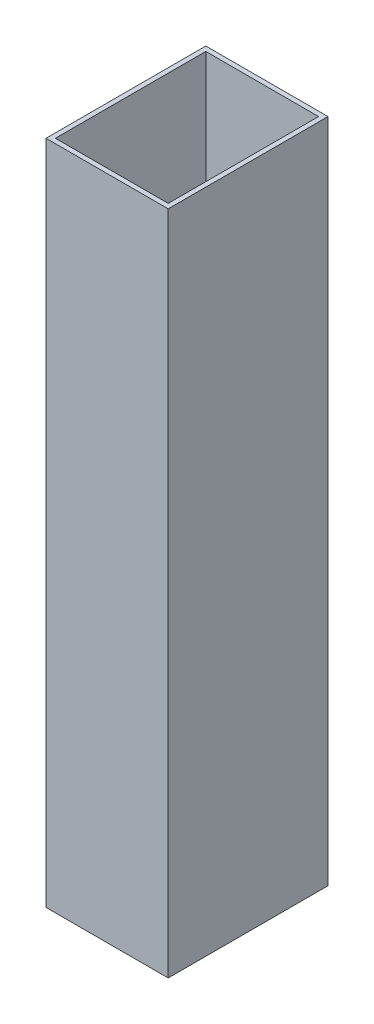
SolidWorks part; units mm, degrees
ref_plane "Plan de face" through (0, 0, 0) normal (0, 0, 1) x (1, 0, 0)
ref_plane "Plan de dessus" through (0, 0, 0) normal (0, 1, 0) x (1, 0, 0)
ref_plane "Plan de droite" through (0, 0, 0) normal (1, 0, 0) x (0, 0, -1)
sketch "Esquisse1" plane through (0, 0, 0) normal (0, 0, 1) x (1, 0, 0)
  line L1 (-41.275, 225) -> (41.275, 225)
  line L2 (-41.275, 225) -> (-41.275, -225)
  line L3 (-41.275, -225) -> (41.275, -225)
  line L4 (41.275, 225) -> (41.275, -225)
  point P4 (0, 225)
  point P6 (41.275, 0)
  dimension "D1" = 82.55
  dimension "D2" = 450
extrude "Boss.-Extru.1" add sketch "Esquisse1" along normal blind 107.95
sketch "Esquisse2" plane through (0, 225, 0) normal (0, 1, 0) x (1, 0, 0)
  line L0 (-41.275, -107.95) -> (-41.275, 0) construction
  line L1 (-38.1, -3.175) -> (38.1, -3.175)
  line L2 (-38.1, -3.175) -> (-38.1, -104.775)
  line L3 (-38.1, -104.775) -> (38.1, -104.775)
  line L4 (38.1, -3.175) -> (38.1, -104.775)
  line L5 (41.275, -107.95) -> (-41.275, -107.95) construction
  line L6 (41.275, 0) -> (-41.275, 0) construction
  line L7 (41.275, -107.95) -> (41.275, 0) construction
  dimension "D1" = 3.175
  dimension "D2" = 3.175
  dimension "D3" = 3.175
  dimension "D4" = 3.175
extrude "Enlèv. mat.-Extru.1" cut sketch "Esquisse2" against normal up to surface (450 mm away) up to face at (0, -225, 53.975)
